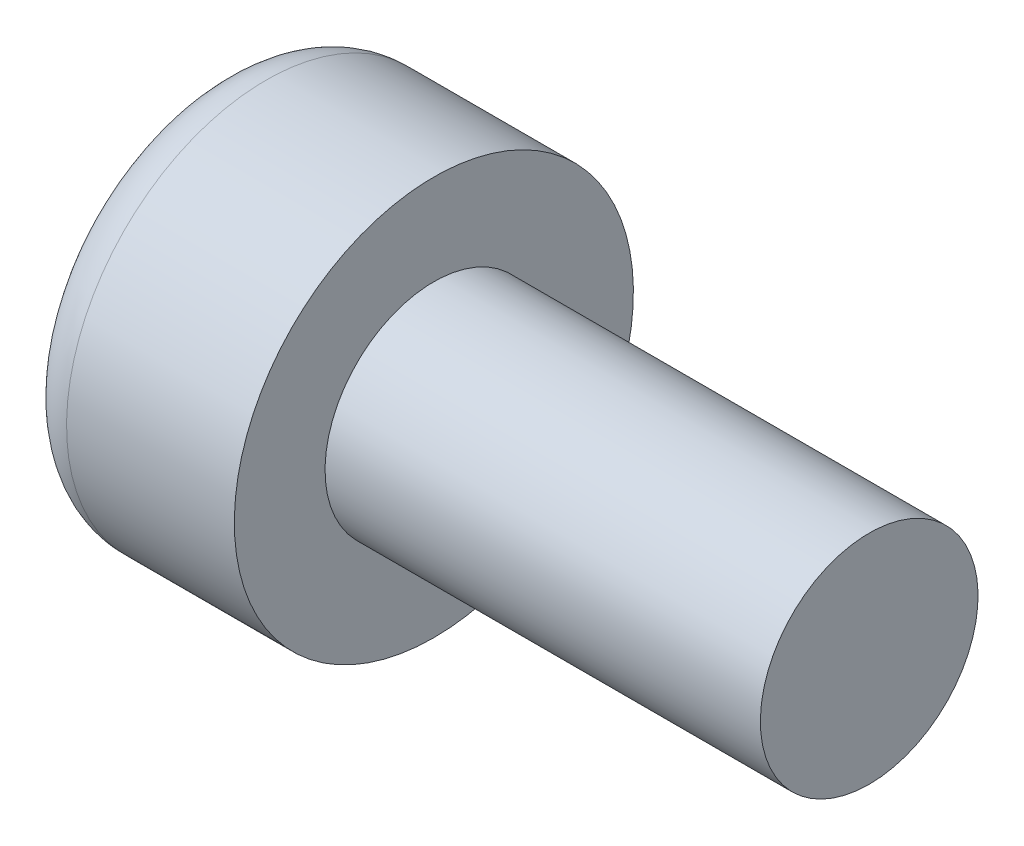
SolidWorks part; units mm, degrees
material "Plain Carbon Steel"
ref_plane "Front Plane" through (0, 0, 0) normal (0, 0, 1) x (1, 0, 0)
ref_plane "Top Plane" through (0, 0, 0) normal (0, 1, 0) x (1, 0, 0)
ref_plane "Right Plane" through (0, 0, 0) normal (1, 0, 0) x (0, 0, -1)
sketch "Sketch1" plane through (0, 0, 0) normal (0, 0, 1) x (1, 0, 0)
  line L0 (0, 0) -> (0, 2.0625)
  line L1 (0.6875, 2.75) -> (3, 2.75)
  line L2 (3, 2.75) -> (3, 1.5)
  line L3 (3, 1.5) -> (9, 1.5)
  line L4 (9, 1.5) -> (9, 0)
  line L5 (9, 0) -> (0, 0) construction
  line L6 (0.6875, 2.0625) -> (0.6875, 1.375) construction
  line L7 (0.6875, 1.375) -> (0.6875, 0.6875) construction
  line L8 (0.6875, 0.6875) -> (0.6875, 0) construction
  line L9 (0.6875, 2.75) -> (0.6875, 2.0625) construction
  line L10 (0, 0) -> (9, 0)
  arc A0 (0, 2.0625) -> (0.6875, 2.75) centre (0.6875, 2.0625) cw
  dimension "D1" = 3
  dimension "D2" = 5.5
  dimension "D3" = 3
  dimension "D4" = 6
revolve "Revolve1" add sketch "Sketch1" angle 360 about L10
sketch "Sketch2" plane through (0, 0, 0) normal (-1, 0, 0) x (0, 0, 1)
  line L1 (0, 1.4434) -> (-1.25, 0.7217)
  line L2 (-1.25, 0.7217) -> (-1.25, -0.7217)
  line L3 (-1.25, -0.7217) -> (0, -1.4434)
  line L4 (0, -1.4434) -> (1.25, -0.7217)
  line L5 (1.25, -0.7217) -> (1.25, 0.7217)
  line L6 (1.25, 0.7217) -> (0, 1.4434)
  circle A0 centre (0, 0) radius 1.25 construction
  dimension "D1" = 2.5
extrude "Cut-Extrude1" cut sketch "Sketch2" against normal blind 1.5
